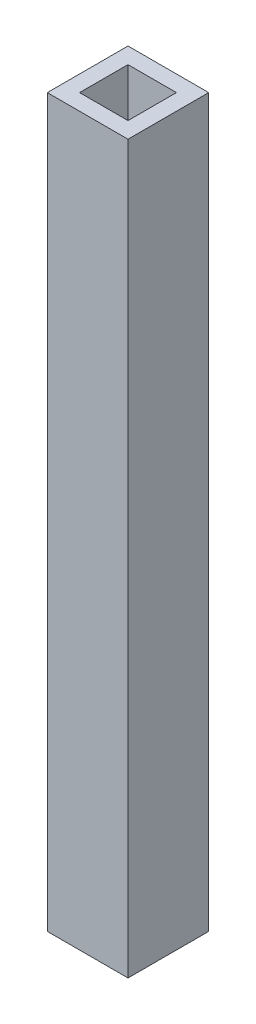
SolidWorks part; units mm, degrees
ref_plane "Front Plane" through (0, 0, 0) normal (0, 0, 1) x (1, 0, 0)
ref_plane "Top Plane" through (0, 0, 0) normal (0, 1, 0) x (1, 0, 0)
ref_plane "Right Plane" through (0, 0, 0) normal (1, 0, 0) x (0, 0, -1)
sketch "Sketch1" plane through (0, 0, 0) normal (0, 1, 0) x (1, 0, 0)
  line L1 (-5, -5) -> (5, -5)
  line L2 (-5, -5) -> (-5, 5)
  line L3 (-5, 5) -> (5, 5)
  line L4 (5, -5) -> (5, 5)
  line L5 (-5, -5) -> (5, 5) construction
  line L6 (-5, 5) -> (5, -5) construction
  point P0 (0, 0)
  dimension "D1" = 10
  dimension "D2" = 10
extrude "Extrude-Thin1" add sketch "Sketch1" along normal blind 90 thin thin type one direction reverse wall 2
